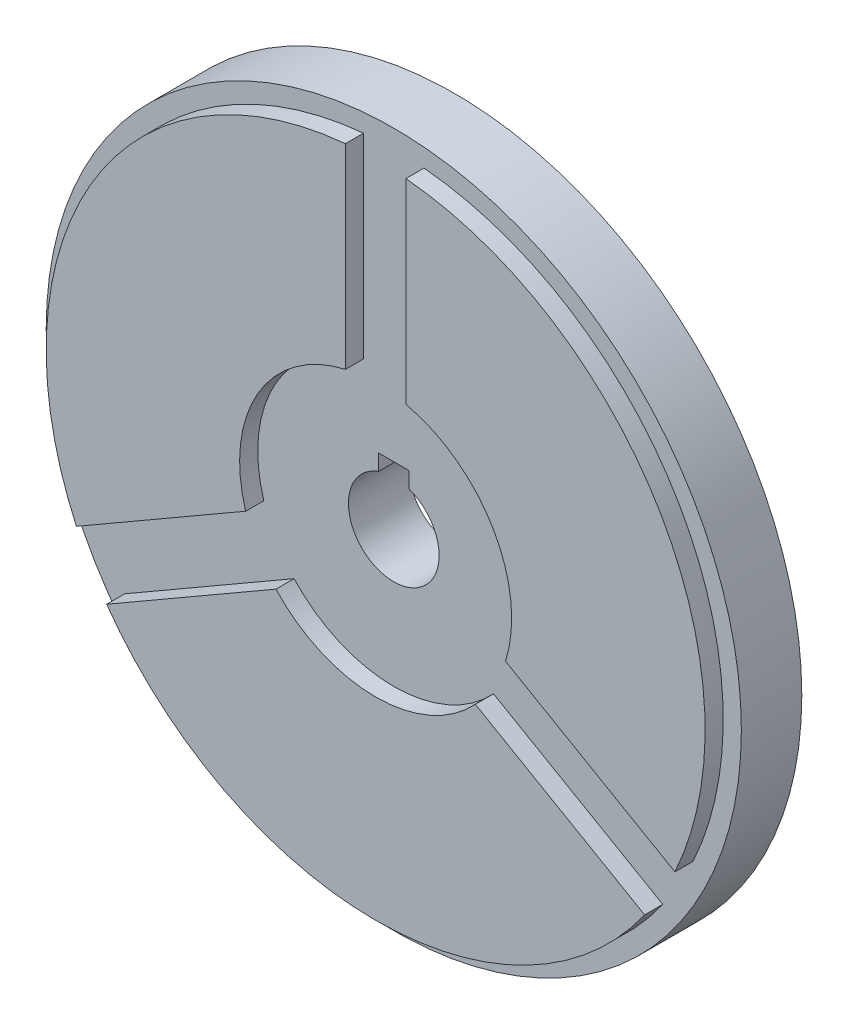
SolidWorks part; units mm, degrees
material "AISI 1020"
ref_plane "Plano frontal" through (0, 0, 0) normal (0, 0, 1) x (1, 0, 0)
ref_plane "Plano superior" through (0, 0, 0) normal (0, 1, 0) x (1, 0, 0)
ref_plane "Plano direito" through (0, 0, 0) normal (1, 0, 0) x (0, 0, -1)
sketch "Esboço1" plane through (0, 0, 0) normal (0, 0, 1) x (1, 0, 0)
  circle A0 centre (0, 0) radius 57.5
  circle A1 centre (0, 0) radius 7.5
  dimension "D1" = 15
  dimension "D2" = 115
extrude "Extrusão1" add sketch "Esboço1" against normal blind 10
sketch "Esboço2" plane through (0, 0, 0) normal (0, 0, 1) x (1, 0, 0)
  line L0 (0, 22.5) -> (0, 54.5) construction
  line L1 (5, 21.9374) -> (5, 54.2702)
  line L2 (-5, 21.9374) -> (-5, 54.2702)
  line L3 (-5, 22.5) -> (-5, 54.5) construction
  line L4 (5, 22.5) -> (5, 54.5) construction
  line L5 (16.4984, -15.2988) -> (44.4993, -31.4652)
  line L6 (21.4984, -6.6386) -> (49.4993, -22.805)
  line L7 (19.4856, -11.25) -> (47.1984, -27.25) construction
  line L8 (-21.4984, -6.6386) -> (-49.4993, -22.805)
  line L9 (-16.4984, -15.2988) -> (-44.4993, -31.4652)
  line L10 (-19.4856, -11.25) -> (-47.1984, -27.25) construction
  circle A2 centre (0, 0) radius 54.5
  circle A3 centre (0, 0) radius 54.5
  circle A5 centre (0, 0) radius 22.5
  circle A6 centre (0, 0) radius 22.5
  dimension "D1" = 3
  dimension "D2" = 15
  dimension "D3" = 5
  dimension "D4" = 5
extrude "Extrusão2" add sketch "Esboço2" along normal blind 3 contours A6 L6 A3 L1 | A6 L2 A3 L8 | A6 L9 A3 L5
sketch "Esboço3" plane through (0, 0, 0) normal (0, 0, 1) x (1, 0, 0)
  line L0 (-2.5, 0) -> (-2.5, 9.7)
  line L1 (-2.5, 0) -> (2.5, 0)
  line L2 (0, 0) -> (0, 9.7) construction
  line L3 (-2.5, 9.7) -> (2.5, 9.7)
  line L4 (2.5, 0) -> (2.5, 9.7)
  circle A0 centre (0, 0) radius 7.5 construction
  dimension "D1" = 5
  dimension "D2" = 9.7
extrude "Corte-extrusão1" cut sketch "Esboço3" against normal through all
